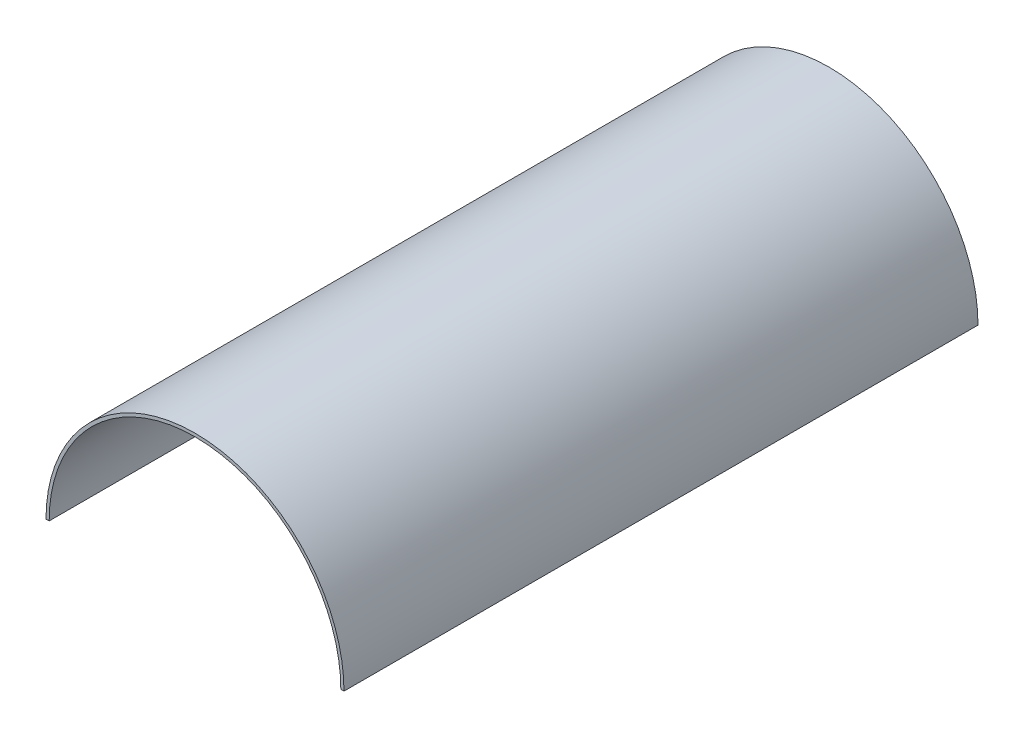
SolidWorks part; units mm, degrees
ref_plane "Alzado" through (0, 0, 0) normal (0, 0, 1) x (1, 0, 0)
ref_plane "Planta" through (0, 0, 0) normal (0, 1, 0) x (1, 0, 0)
ref_plane "Vista lateral" through (0, 0, 0) normal (1, 0, 0) x (0, 0, -1)
sketch "Croquis1" plane through (0, 0, 0) normal (0, 0, 1) x (1, 0, 0)
  circle A0 centre (0, 0) radius 23.5
  circle A1 centre (0, 0) radius 23
  dimension "D1" = 47
  dimension "D2" = 0.5
extrude "Saliente-Extruir1" add sketch "Croquis1" along normal blind 100
sketch "Croquis2" plane through (0, 0, 0) normal (0, 1, 0) x (1, 0, 0)
  line L1 (-25.4056, -103.1805) -> (26.089, -103.1805)
  line L2 (-25.4056, -103.1805) -> (-25.4056, 11.6122)
  line L3 (-25.4056, 11.6122) -> (26.089, 11.6122)
  line L4 (26.089, -103.1805) -> (26.089, 11.6122)
extrude "Cortar-Extruir1" cut sketch "Croquis2" against normal through all
